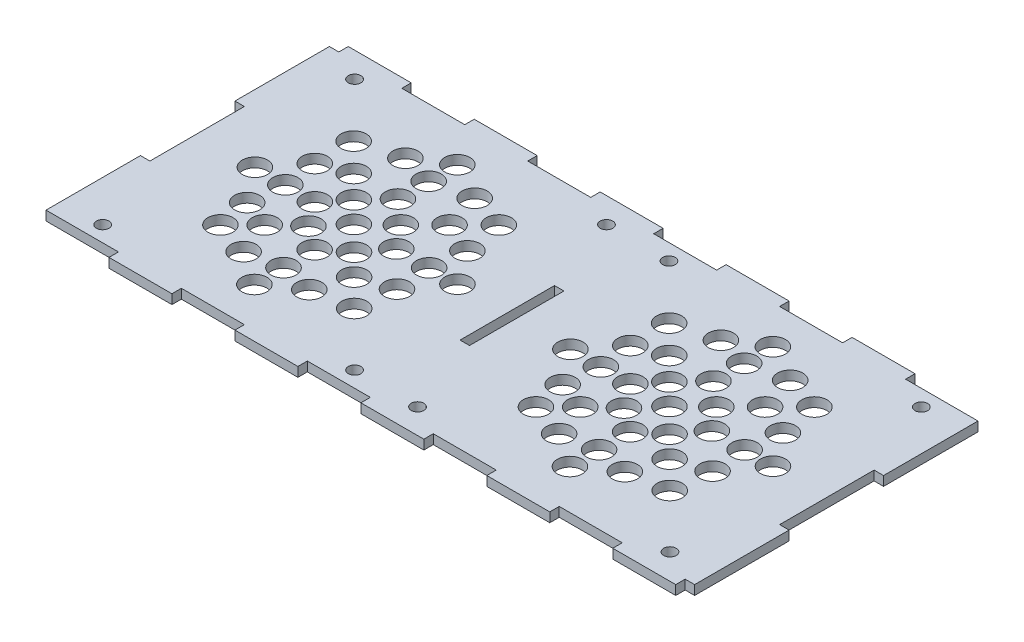
SolidWorks part; units mm, degrees
ref_plane "Front Plane" through (0, 0, 0) normal (0, 0, 1) x (1, 0, 0)
ref_plane "Top Plane" through (0, 0, 0) normal (0, 1, 0) x (1, 0, 0)
ref_plane "Right Plane" through (0, 0, 0) normal (1, 0, 0) x (0, 0, -1)
sketch "Sketch1" plane through (0, 0, 0) normal (0, 1, 0) x (1, 0, 0)
  line L0 (-53.1892, 52.9189) -> (-53.1892, 55.9189)
  line L1 (-73.1892, 52.9189) -> (-53.1892, 52.9189)
  line L2 (-93.1892, 22.9189) -> (-93.1892, -7.0811)
  line L3 (-93.1892, -37.0811) -> (-73.1892, -37.0811)
  line L4 (106.8108, 22.9189) -> (106.8108, -7.0811)
  line L5 (106.8108, -7.0811) -> (109.8108, -7.0811)
  line L6 (-93.1892, 52.9189) -> (-93.1892, 55.9189)
  line L7 (-93.1892, 55.9189) -> (-73.1892, 55.9189)
  line L8 (-73.1892, 52.9189) -> (-73.1892, 55.9189)
  line L9 (-53.1892, 55.9189) -> (-33.1892, 55.9189)
  line L10 (-33.1892, 52.9189) -> (-33.1892, 55.9189)
  line L11 (-13.1892, 52.9189) -> (-13.1892, 55.9189)
  line L12 (-13.1892, 55.9189) -> (6.8108, 55.9189)
  line L13 (6.8108, 52.9189) -> (6.8108, 55.9189)
  line L14 (26.8108, 52.9189) -> (26.8108, 55.9189)
  line L15 (26.8108, 55.9189) -> (46.8108, 55.9189)
  line L16 (46.8108, 52.9189) -> (46.8108, 55.9189)
  line L17 (66.8108, 52.9189) -> (66.8108, 55.9189)
  line L18 (66.8108, 55.9189) -> (86.8108, 55.9189)
  line L19 (86.8108, 52.9189) -> (86.8108, 55.9189)
  line L20 (86.8108, 52.9189) -> (106.8108, 52.9189)
  line L21 (46.8108, 52.9189) -> (66.8108, 52.9189)
  line L22 (6.8108, 52.9189) -> (26.8108, 52.9189)
  line L23 (-33.1892, 52.9189) -> (-13.1892, 52.9189)
  line L24 (106.8108, 52.9189) -> (109.8108, 52.9189)
  line L25 (66.8108, -37.0811) -> (66.8108, -40.0811)
  line L26 (106.8108, 22.9189) -> (109.8108, 22.9189)
  line L27 (109.8108, 52.9189) -> (109.8108, 22.9189)
  line L28 (109.8108, -7.0811) -> (109.8108, -37.0811)
  line L29 (106.8108, -37.0811) -> (109.8108, -37.0811)
  line L30 (-93.1892, 22.9189) -> (-96.1892, 22.9189)
  line L31 (106.8108, -37.0811) -> (106.8108, -40.0811)
  line L32 (106.8108, -40.0811) -> (86.8108, -40.0811)
  line L33 (86.8108, -37.0811) -> (86.8108, -40.0811)
  line L34 (66.8108, -40.0811) -> (46.8108, -40.0811)
  line L35 (46.8108, -37.0811) -> (46.8108, -40.0811)
  line L36 (26.8108, -37.0811) -> (26.8108, -40.0811)
  line L37 (26.8108, -40.0811) -> (6.8108, -40.0811)
  line L38 (6.8108, -37.0811) -> (6.8108, -40.0811)
  line L39 (-13.1892, -37.0811) -> (-13.1892, -40.0811)
  line L40 (-13.1892, -40.0811) -> (-33.1892, -40.0811)
  line L41 (-33.1892, -37.0811) -> (-33.1892, -40.0811)
  line L42 (-53.1892, -37.0811) -> (-53.1892, -40.0811)
  line L43 (-53.1892, -40.0811) -> (-73.1892, -40.0811)
  line L44 (-73.1892, -37.0811) -> (-73.1892, -40.0811)
  line L45 (-53.1892, -37.0811) -> (-33.1892, -37.0811)
  line L46 (-13.1892, -37.0811) -> (6.8108, -37.0811)
  line L47 (26.8108, -37.0811) -> (46.8108, -37.0811)
  line L48 (66.8108, -37.0811) -> (86.8108, -37.0811)
  line L49 (-93.1892, -37.0811) -> (-96.1892, -37.0811)
  line L50 (6.8108, 83.4508) -> (6.8108, 22.9189) construction
  line L51 (-93.1892, -7.0811) -> (-96.1892, -7.0811)
  line L52 (-96.1892, -37.0811) -> (-96.1892, -7.0811)
  line L53 (-96.1892, 22.9189) -> (-96.1892, 52.9189)
  line L54 (-93.1892, 52.9189) -> (-96.1892, 52.9189)
  line L55 (8.3108, 22.9189) -> (8.3108, -7.0811)
  line L56 (8.3108, 22.9189) -> (5.3108, 22.9189)
  line L57 (6.8108, -7.0811) -> (6.8108, -61.0694) construction
  line L58 (8.3108, -7.0811) -> (5.3108, -7.0811)
  line L59 (5.3108, 22.9189) -> (5.3108, -7.0811)
  dimension "D1" = 30
  dimension "D2" = 30
extrude "Boss-Extrude1" add sketch "Sketch1" along normal blind 3
sketch "Sketch2" plane through (0, 3, 0) normal (0, 1, 0) x (1, 0, 0)
  line L1 (6.8108, 63.729) -> (6.8108, -47.4814) construction
  circle A0 centre (-83.1892, 47.9189) radius 2
  circle A1 centre (-83.1892, -32.0811) radius 2
  circle A2 centre (-3.1892, 47.9189) radius 2
  circle A3 centre (-3.1892, -32.0811) radius 2
  circle A4 centre (96.9752, 47.7538) radius 2
  circle A5 centre (96.8907, -31.9998) radius 2
  circle A6 centre (16.731, 47.8377) radius 2
  circle A7 centre (16.9296, -32.2) radius 2
  circle A10 centre (64.4095, 15.2255) radius 4
  circle A11 centre (64.459, 0.3015) radius 4
  circle A12 centre (72.1506, 22.9576) radius 4
  circle A13 centre (79.9849, 30.783) radius 4
  circle A14 centre (42.7822, -6.3771) radius 4
  circle A15 centre (35.7447, -13.4064) radius 4
  circle A16 centre (50.0316, 0.2519) radius 4
  circle A17 centre (71.3287, -6.5407) radius 4
  circle A18 centre (56.8108, 7.9189) radius 4
  circle A19 centre (79.9849, -15.162) radius 4
  circle A20 centre (50.0316, 14.6709) radius 4
  circle A21 centre (42.7822, 21.8912) radius 4
  circle A22 centre (33.8545, 30.783) radius 4
  circle A23 centre (70.2869, 7.9189) radius 4
  circle A24 centre (80.6959, 7.9189) radius 4
  circle A25 centre (89.6983, 7.9189) radius 4
  circle A26 centre (35.0277, 7.9189) radius 4
  circle A27 centre (44.4051, 7.9189) radius 4
  circle A28 centre (25.3689, 7.9189) radius 4
  circle A29 centre (57.5336, -5.2808) radius 4
  circle A30 centre (57.5336, -15.162) radius 4
  circle A31 centre (57.5336, -24.4109) radius 4
  circle A32 centre (56.8108, 21.8912) radius 4
  circle A33 centre (56.8108, 31.6664) radius 4
  circle A34 centre (56.8108, 40.7625) radius 4
  circle A35 centre (33.8545, 18.4442) radius 4
  circle A36 centre (46.7822, 34.2921) radius 4
  circle A37 centre (68.7865, 34.2921) radius 4
  circle A38 centre (82.1025, 18.6709) radius 4
  circle A39 centre (81.4461, -3.0302) radius 4
  circle A40 centre (67.6612, -17.0964) radius 4
  circle A41 centre (46.7822, -17.0964) radius 4
  circle A42 centre (33.8545, -3.0302) radius 4
  circle A43 centre (-35.7614, 15.1877) radius 4
  circle A44 centre (-35.712, 0.2637) radius 4
  circle A45 centre (-28.0204, 22.9199) radius 4
  circle A46 centre (-20.186, 30.7452) radius 4
  circle A47 centre (-57.3888, -6.4148) radius 4
  circle A48 centre (-64.4262, -13.4442) radius 4
  circle A49 centre (-50.1393, 0.2141) radius 4
  circle A50 centre (-28.8422, -6.5784) radius 4
  circle A51 centre (-43.3601, 7.8811) radius 4
  circle A52 centre (-20.186, -15.1998) radius 4
  circle A53 centre (-50.1393, 14.6331) radius 4
  circle A54 centre (-57.3888, 21.8534) radius 4
  circle A55 centre (-66.3165, 30.7452) radius 4
  circle A56 centre (-29.884, 7.8811) radius 4
  circle A57 centre (-19.475, 7.8811) radius 4
  circle A58 centre (-10.4727, 7.8811) radius 4
  circle A59 centre (-65.1433, 7.8811) radius 4
  circle A60 centre (-55.7658, 7.8811) radius 4
  circle A61 centre (-74.8021, 7.8811) radius 4
  circle A62 centre (-42.6374, -5.3186) radius 4
  circle A63 centre (-42.6374, -15.1998) radius 4
  circle A64 centre (-42.6374, -24.4486) radius 4
  circle A65 centre (-43.3601, 21.8534) radius 4
  circle A66 centre (-43.3601, 31.6286) radius 4
  circle A67 centre (-43.3601, 40.7248) radius 4
  circle A68 centre (-66.3165, 18.4064) radius 4
  circle A69 centre (-53.3888, 34.2543) radius 4
  circle A70 centre (-31.3844, 34.2543) radius 4
  circle A71 centre (-18.0684, 18.6331) radius 4
  circle A72 centre (-18.7248, -3.068) radius 4
  circle A73 centre (-32.5097, -17.1342) radius 4
  circle A74 centre (-53.3888, -17.1342) radius 4
  circle A75 centre (-66.3165, -3.068) radius 4
extrude "Cut-Extrude1" cut sketch "Sketch2" against normal blind 3
